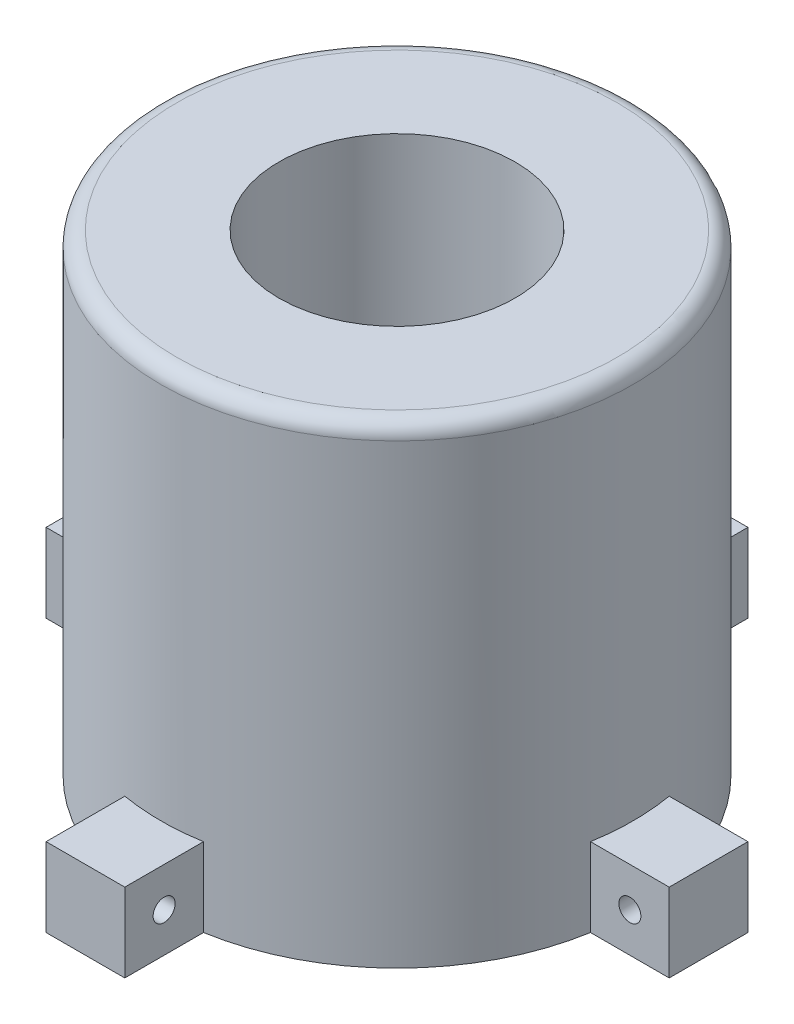
SolidWorks part; units mm, degrees
ref_plane "Front Plane" through (0, 0, 0) normal (0, 0, 1) x (1, 0, 0)
ref_plane "Top Plane" through (0, 0, 0) normal (0, 1, 0) x (1, 0, 0)
ref_plane "Right Plane" through (0, 0, 0) normal (1, 0, 0) x (0, 0, -1)
sketch "Sketch2" plane through (0, 0, 0) normal (0, 1, 0) x (1, 0, 0)
  circle A0 centre (0, 0) radius 38.1
  dimension "D1" = 76.2
extrude "Boss-Extrude1" add sketch "Sketch2" along normal blind 76.2
sketch "Sketch3" plane through (0, 76.2, 0) normal (0, 1, 0) x (1, 0, 0)
  circle A0 centre (0, 0) radius 19.05
  dimension "D1" = 38.1
extrude "Cut-Extrude1" cut sketch "Sketch3" against normal blind 76.2
fillet "Fillet1" radius 2.54 1 edges at (0, 76.2, 38.1)
sketch "Sketch4" plane through (0, 0, 0) normal (0, 1, 0) x (1, 0, 0)
  line L0 (-37.5671, 6.35) -> (-50.2671, 6.35)
  line L1 (-50.2671, 6.35) -> (-50.2671, -6.35)
  line L2 (-50.2671, -6.35) -> (-37.5671, -6.35)
  arc A0 (-37.5671, 6.35) -> (-37.5671, -6.35) centre (0, 0) ccw
  circle A1 centre (0, 0) radius 38.1 construction
  dimension "D1" = 12.7
  dimension "D2" = 12.7
  dimension "D3" = 12.7
extrude "Boss-Extrude2" add sketch "Sketch4" along normal blind 12.7
sketch "Sketch5" plane through (0, 0, 6.35) normal (0, 0, 1) x (1, 0, 0)
  line L0 (-50.2671, 12.7) -> (-37.5671, 12.7) construction
  line L1 (-50.2671, 12.7) -> (-50.2671, 0) construction
  circle A0 centre (-43.9171, 6.35) radius 1.778
  point P4 (-43.9171, 12.7)
  point P7 (-50.2671, 6.35)
  dimension "D1" = 3.556
extrude "Cut-Extrude2" cut sketch "Sketch5" against normal blind 25.4
pattern_circular "CirPattern2" count 4 over 360 about axis through (0, 0, 0) along (0, 1, 0) of "Boss-Extrude2", "Cut-Extrude2"
